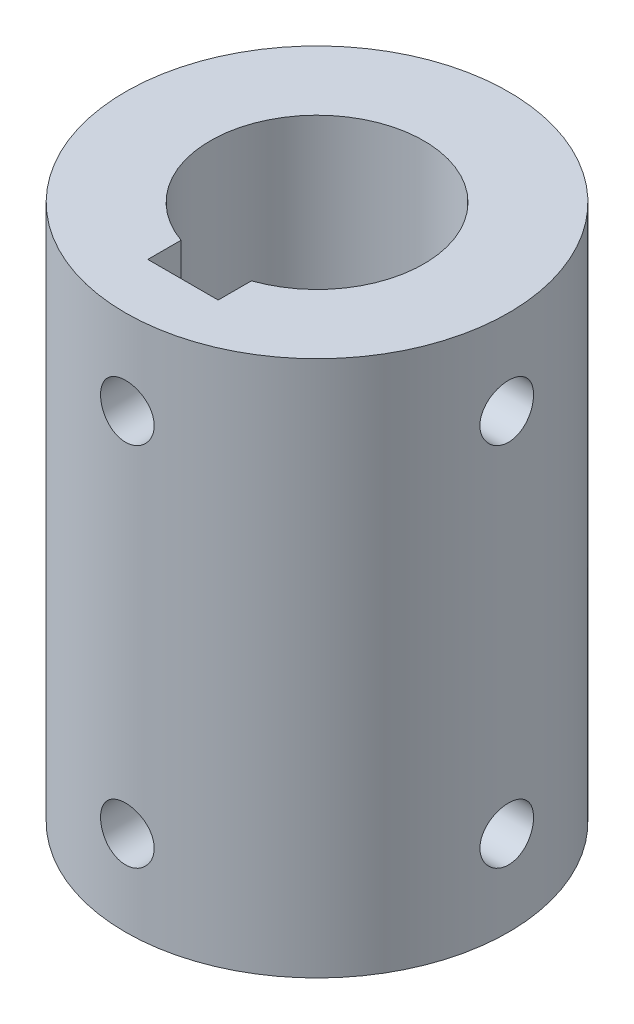
SolidWorks part; units mm, degrees
ref_plane "Front" through (0, 0, 0) normal (0, 0, 1) x (1, 0, 0)
ref_plane "Top" through (0, 0, 0) normal (0, 1, 0) x (1, 0, 0)
ref_plane "Right" through (0, 0, 0) normal (1, 0, 0) x (0, 0, -1)
sketch "Sketch1" plane through (0, 0, 0) normal (0, 1, 0) x (1, 0, 0)
  circle A0 centre (0, 0) radius 14.2875
  dimension "D1" = 28.575
extrude "Boss-Extrude1" add sketch "Sketch1" along normal blind 40
sketch "Sketch2" plane through (0, 0, 0) normal (0, -1, 0) x (-1, 0, 0)
  circle A0 centre (0, 0) radius 6.3754
  dimension "D1" = 12.7508
extrude "Cut-Extrude1" cut sketch "Sketch2" against normal up to next
sketch "Sketch3" plane through (0, 40, 0) normal (0, 1, 0) x (1, 0, 0)
  circle A0 centre (0, 0) radius 7.9629
  dimension "D1" = 15.9258
extrude "Cut-Extrude2" cut sketch "Sketch3" against normal blind 20
sketch "Sketch4" plane through (0, 40, 0) normal (0, 1, 0) x (1, 0, 0)
  line L0 (0, 0) -> (0, -10) construction
  line L1 (2.625, -10) -> (-2.625, -10)
  line L2 (2.625, -10) -> (2.625, -7.5178)
  line L3 (-2.625, -10) -> (-2.625, -7.5178)
  circle A0 centre (0, 0) radius 7.9629 construction
  circle A1 centre (0, 0) radius 7.9629 construction
  arc A2 (-2.625, -7.5178) -> (2.625, -7.5178) centre (0, 0) ccw
  dimension "D1" = 5.25
  dimension "D2" = 10
extrude "Cut-Extrude3" cut sketch "Sketch4" against normal up to surface (20 mm away) up to face at (0, 20, 7.9629)
sketch "Sketch5" plane through (0, 0, 0) normal (0, 0, 1) x (1, 0, 0)
  line L0 (0, 40) -> (0, 0) construction
  line L1 (14.2875, 40) -> (-14.2875, 40) construction
  line L2 (-14.2875, 0) -> (14.2875, 0) construction
  circle A0 centre (0, 33.65) radius 2
  circle A1 centre (0, 6.35) radius 2
  dimension "D1" = 4
  dimension "D2" = 6.35
  dimension "D3" = 6.35
extrude "Cut-Extrude4" cut sketch "Sketch5" along normal up to surface (14.1468 mm away)
pattern_circular "CirPattern1" count 2 over 90 about axis through (0, 40, 0) along (0, 1, 0) of "Cut-Extrude4"
